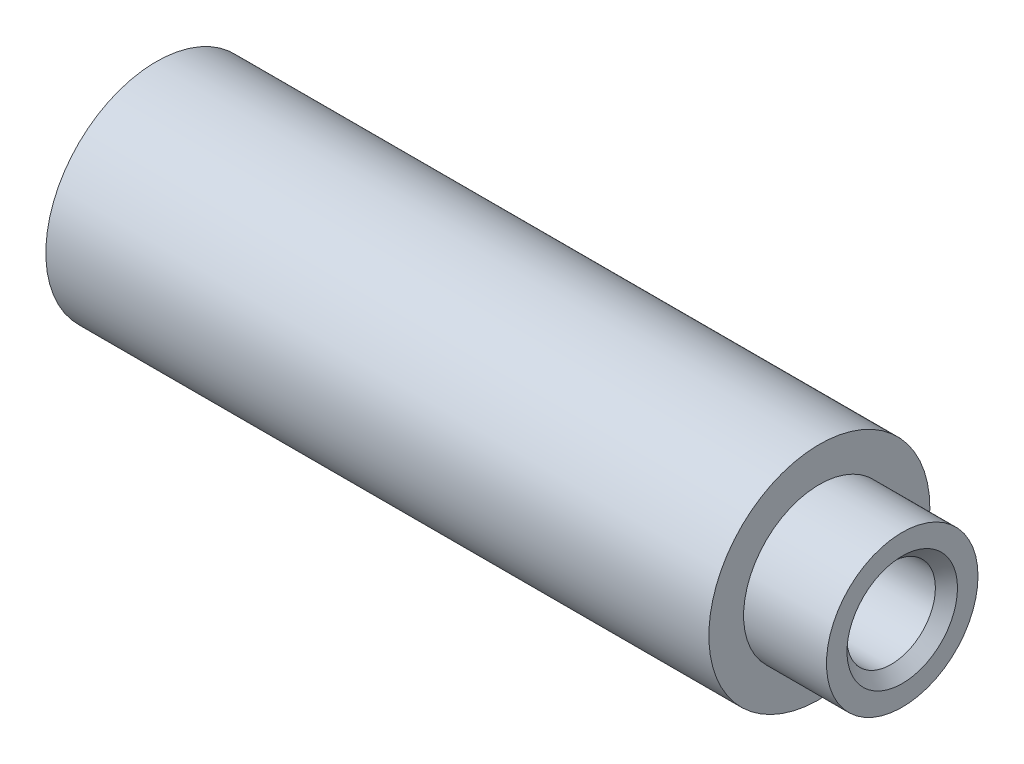
SolidWorks part; units mm, degrees
ref_plane "Ebene vorne" through (0, 0, 0) normal (0, 0, 1) x (1, 0, 0)
ref_plane "Ebene oben" through (0, 0, 0) normal (0, 1, 0) x (1, 0, 0)
ref_plane "Ebene rechts" through (0, 0, 0) normal (1, 0, 0) x (0, 0, -1)
sketch "Skizze1" plane through (0, 0, 0) normal (1, 0, 0) x (0, 0, -1)
  circle A0 centre (0, 0) radius 1.6
  circle A1 centre (0, 0) radius 4
  dimension "D1" = 8
  dimension "D2" = 3.2
extrude "Aufsatz-Linear austragen1" add sketch "Skizze1" along normal blind 27
sketch "Skizze2" plane through (27, 0, 0) normal (1, 0, 0) x (0, 0, -1)
  circle A0 centre (0, 0) radius 2.7425
  dimension "D1" = 5.485
extrude "Schnitt-Linear austragen1" cut sketch "Skizze2" against normal blind 3 flip side to cut
chamfer "Fase1" distance 0.4 angle 45 2 edges at (0, 0, -1.6) (27, 0, -1.6)
